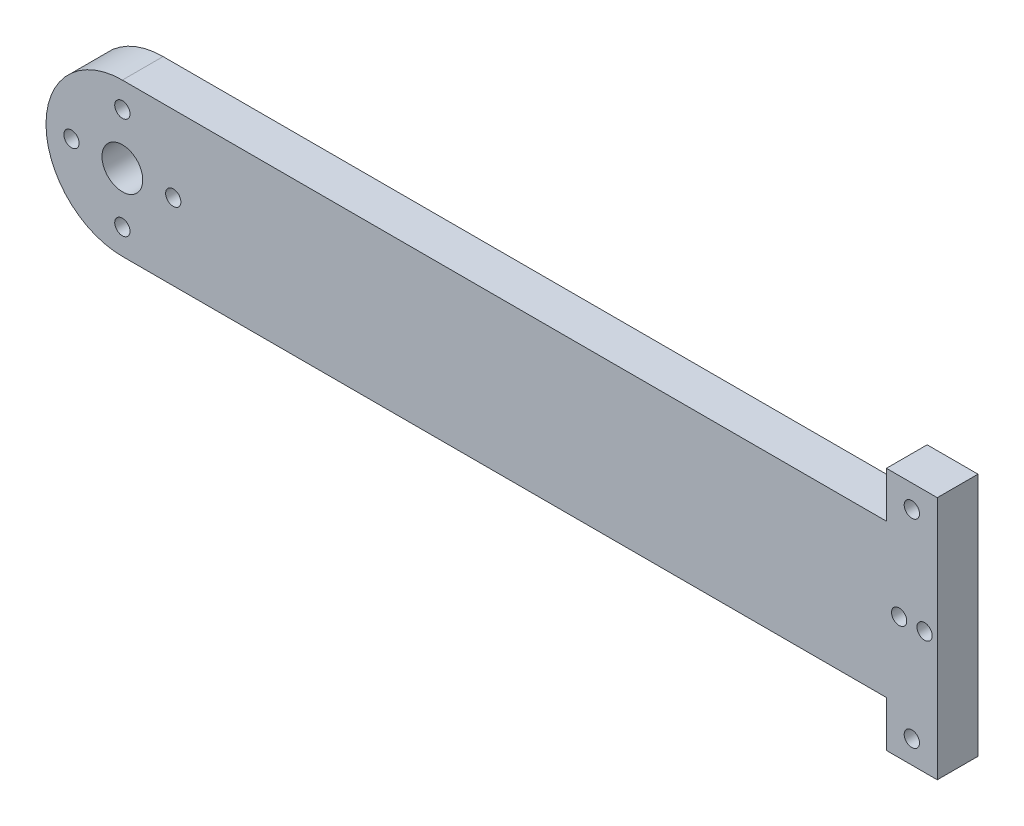
SolidWorks part; units mm, degrees
ref_plane "Front Plane" through (0, 0, 0) normal (0, 0, 1) x (1, 0, 0)
ref_plane "Top Plane" through (0, 0, 0) normal (0, 1, 0) x (1, 0, 0)
ref_plane "Right Plane" through (0, 0, 0) normal (1, 0, 0) x (0, 0, -1)
sketch "Sketch3" plane through (0, 0, 0) normal (0, 0, 1) x (1, 0, 0)
  line L0 (0, -42.2189) -> (150.107, -42.2189)
  line L1 (150.107, -42.2189) -> (150.107, -51.2231)
  line L2 (0, -12.2154) -> (150.107, -12.2154)
  line L3 (150.107, -51.2231) -> (155.1029, -51.2231)
  line L4 (155.1029, -51.2231) -> (160.1001, -51.2231)
  line L5 (150.107, -12.2154) -> (150.107, -3.2147)
  line L6 (150.107, -3.2147) -> (155.1029, -3.2147)
  line L7 (155.1029, -3.2147) -> (160.1001, -3.2147)
  line L8 (160.1001, -3.2147) -> (160.1001, -51.2231)
  arc A0 (0, -12.2154) -> (0, -42.2189) centre (0, -27.2171) ccw
  circle A1 centre (0, -27.2171) radius 4.0048
  circle A2 centre (0, -37.214) radius 1.5007
  circle A3 centre (0, -17.2195) radius 1.5029
  circle A4 centre (9.9966, -27.2171) radius 1.4955
  circle A5 centre (-9.9959, -27.2171) radius 1.5015
  circle A6 centre (155.1029, -46.721) radius 1.5044
  circle A7 centre (155.1029, -7.715) radius 1.5037
  circle A8 centre (152.6049, -27.2171) radius 1.4954
  circle A9 centre (157.6015, -27.2171) radius 1.4975
  dimension "D1" = 30.0035
  dimension "D2" = 150.107
  dimension "D3" = 30.0035
  dimension "D4" = 48.0084
sketch "Sketch5" plane through (0, 0, 0) normal (0, 0, 1) x (1, 0, 0)
  line L0 (0, -42.2189) -> (150.107, -42.2189)
  line L1 (150.107, -42.2189) -> (150.107, -51.2231)
  line L2 (0, -12.2154) -> (150.107, -12.2154)
  line L3 (150.107, -51.2231) -> (155.1029, -51.2231)
  line L4 (155.1029, -51.2231) -> (160.1001, -51.2231)
  line L5 (150.107, -12.2154) -> (150.107, -3.2147)
  line L6 (150.107, -3.2147) -> (155.1029, -3.2147)
  line L7 (155.1029, -3.2147) -> (160.1001, -3.2147)
  line L8 (160.1001, -3.2147) -> (160.1001, -51.2231)
  arc A0 (0, -12.2154) -> (0, -42.2189) centre (0, -27.2171) ccw
extrude "Boss-Extrude1" add sketch "Sketch5" along normal blind 8
sketch "Sketch6" plane through (0, 0, 0) normal (0, 0, 1) x (1, 0, 0)
  circle A0 centre (0, -27.2171) radius 4.0048
  circle A1 centre (0, -37.214) radius 1.5007
  circle A2 centre (0, -17.2195) radius 1.5029
  circle A3 centre (9.9966, -27.2171) radius 1.4955
  circle A4 centre (-9.9959, -27.2171) radius 1.5015
  circle A5 centre (155.1029, -46.721) radius 1.5044
  circle A6 centre (155.1029, -7.715) radius 1.5037
  circle A7 centre (152.6049, -27.2171) radius 1.4954
  circle A8 centre (157.6015, -27.2171) radius 1.4975
extrude "Cut-Extrude6" cut sketch "Sketch6" against normal blind 8 and the other way through all
